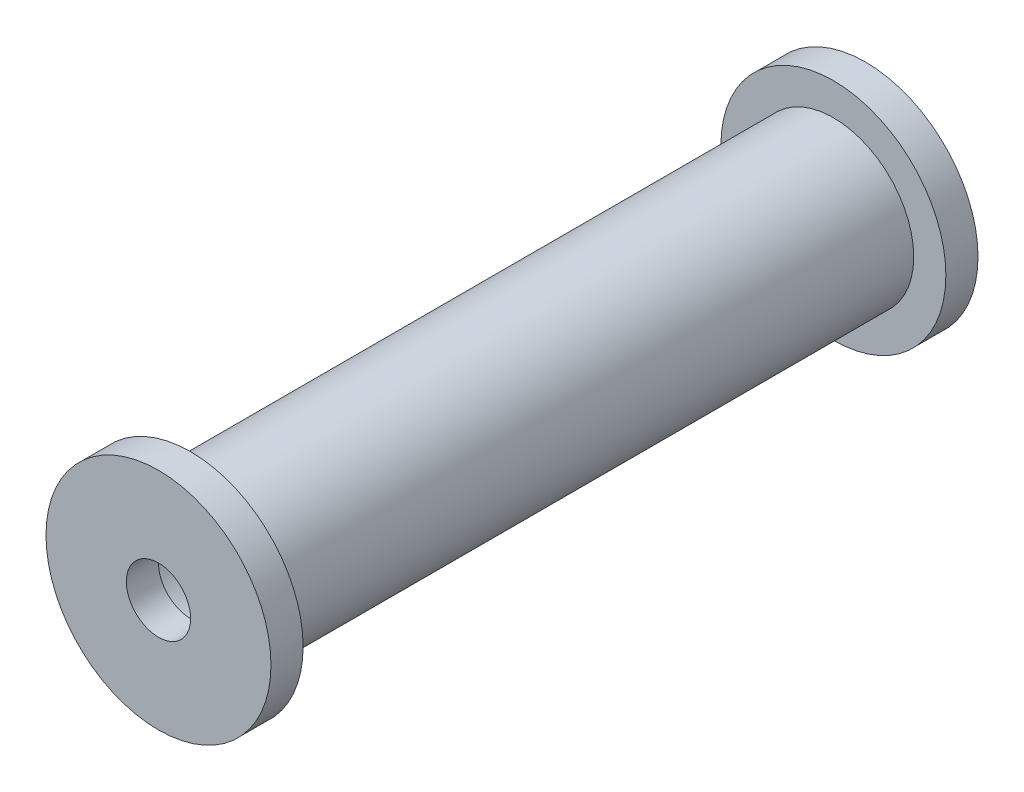
SolidWorks part; units mm, degrees
material "ASTM A36 Steel"
ref_plane "Front Plane" through (0, 0, 0) normal (0, 0, 1) x (1, 0, 0)
ref_plane "Top Plane" through (0, 0, 0) normal (0, 1, 0) x (1, 0, 0)
ref_plane "Right Plane" through (0, 0, 0) normal (1, 0, 0) x (0, 0, -1)
sketch "Sketch1" plane through (0, 0, 0) normal (0, 0, 1) x (1, 0, 0)
  circle A2 centre (0, 0) radius 25
  circle A3 centre (0, 0) radius 20
  dimension "D1" = 50
  dimension "D2" = 40
extrude "Boss-Extrude2" add sketch "Sketch1" along normal blind 200
sketch "Sketch4" plane through (0, 0, 200) normal (0, 0, 1) x (1, 0, 0)
  circle A0 centre (0, 0) radius 35
  circle A1 centre (0, 0) radius 10
  dimension "D1" = 70
  dimension "D2" = 20
extrude "Boss-Extrude3" add sketch "Sketch4" along normal blind 10
sketch "Sketch5" plane through (0, 0, 0) normal (0, 0, -1) x (-1, 0, 0)
  circle A0 centre (0, 0) radius 35
  circle A1 centre (0, 0) radius 10
extrude "Boss-Extrude4" add sketch "Sketch5" along normal blind 10
